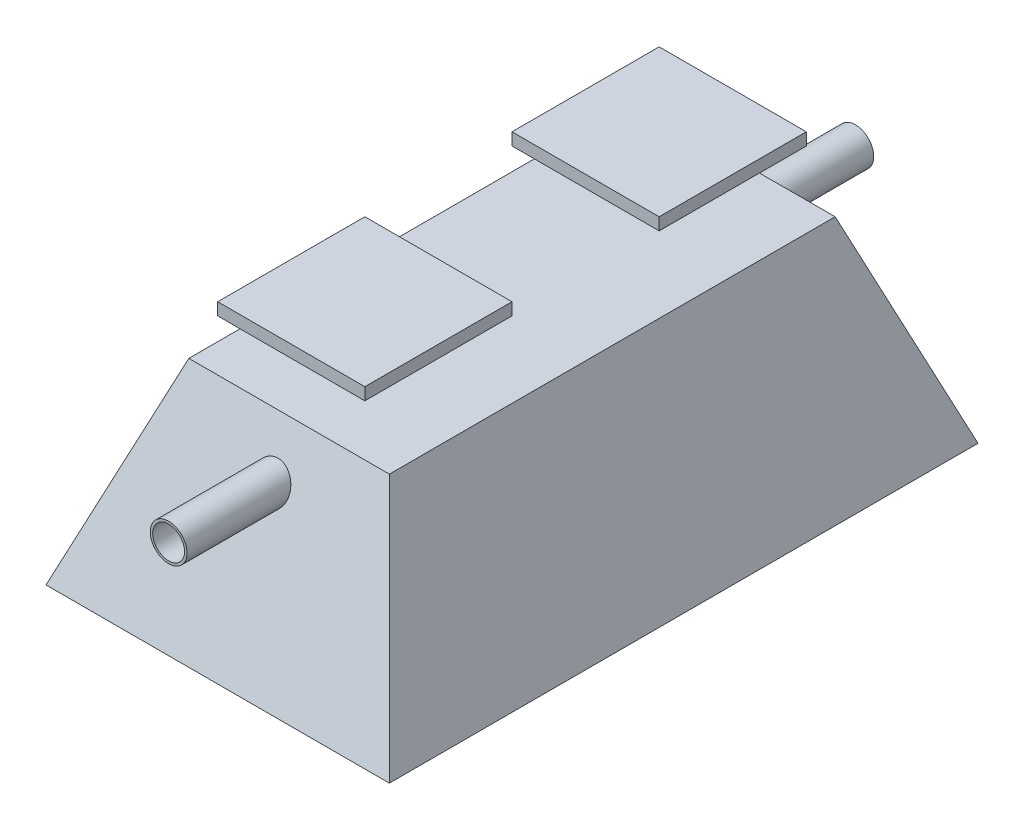
SolidWorks part; units mm, degrees
ref_plane "Front" through (0, 0, 0) normal (0, 0, 1) x (1, 0, 0)
ref_plane "Top" through (0, 0, 0) normal (0, 1, 0) x (1, 0, 0)
ref_plane "Right" through (0, 0, 0) normal (1, 0, 0) x (0, 0, -1)
sketch "Sketch1" plane through (0, 0, 0) normal (0, 1, 0) x (1, 0, 0)
  line L1 (-177.8, 304.8) -> (177.8, 304.8)
  line L2 (-177.8, 304.8) -> (-177.8, -304.8)
  line L3 (-177.8, -304.8) -> (177.8, -304.8)
  line L4 (177.8, 304.8) -> (177.8, -304.8)
  line L5 (-177.8, 304.8) -> (177.8, -304.8) construction
  line L6 (-177.8, -304.8) -> (177.8, 304.8) construction
  point P0 (0, 0)
  dimension "D1" = 609.6
  dimension "D2" = 355.6
extrude "Boss-Extrude1" add sketch "Sketch1" along normal blind 203.2 draft 20
sketch "Sketch2" plane through (0, 0, 0) normal (0, 0, 1) x (1, 0, 0)
  line L0 (0, 152.4) -> (0, 0) construction
  circle A0 centre (0, 152.4) radius 12.7
  circle A1 centre (0, 152.4) radius 19.05
  dimension "D1" = 25.4
  dimension "D3" = 38.1
  dimension "D2" = 152.4
extrude "Boss-Extrude2" add sketch "Sketch2" along normal blind 355.6 and the other way blind 355.6
shell "Shell1" thickness 2.54
sketch "Sketch3" plane through (0, 0, 353.06) normal (0, 0, -1) x (-1, 0, 0)
  circle A1 centre (0, 152.4) radius 16.51
  circle A2 centre (0, 152.4) radius 16.51
  dimension "D1" = 0
extrude "Cut-Extrude1" cut sketch "Sketch3" against normal through all and the other way through all
sketch "Sketch4" plane through (0, 203.2, 0) normal (0, 1, 0) x (1, 0, 0)
  line L0 (0, 0) -> (0, 152.4) construction
  line L1 (0, 0) -> (0, -152.4) construction
  circle A0 centre (0, 152.4) radius 6.35
  circle A1 centre (0, -152.4) radius 6.35
  dimension "D2" = 12.7
  dimension "D3" = 12.7
  dimension "D1" = 152.4
extrude "Boss-Extrude3" add sketch "Sketch4" along normal blind 50.8
sketch "Sketch5" plane through (0, 254, 0) normal (0, 1, 0) x (1, 0, 0)
  line L1 (-76.2, 228.6) -> (76.2, 228.6)
  line L2 (-76.2, 228.6) -> (-76.2, 76.2)
  line L3 (-76.2, 76.2) -> (76.2, 76.2)
  line L4 (76.2, 228.6) -> (76.2, 76.2)
  line L5 (-76.2, 228.6) -> (76.2, 76.2) construction
  line L6 (-76.2, 76.2) -> (76.2, 228.6) construction
  line L7 (-76.2, -76.2) -> (76.2, -76.2)
  line L8 (-76.2, -76.2) -> (-76.2, -228.6)
  line L9 (-76.2, -228.6) -> (76.2, -228.6)
  line L10 (76.2, -76.2) -> (76.2, -228.6)
  line L11 (-76.2, -76.2) -> (76.2, -228.6) construction
  line L12 (-76.2, -228.6) -> (76.2, -76.2) construction
  point P0 (0, 152.4)
  point P6 (0, -152.4)
  dimension "D1" = 152.4
extrude "Boss-Extrude4" add sketch "Sketch5" along normal blind 12.7
sketch "Sketch6" plane through (0, 0, 0) normal (0, -1, 0) x (1, 0, 0)
  line L0 (175.097, -302.097) -> (-175.097, -302.097) construction
  line L1 (175.097, 302.097) -> (175.097, -302.097) construction
  line L2 (-175.097, 302.097) -> (175.097, 302.097) construction
  line L3 (-175.097, -302.097) -> (-175.097, 302.097) construction
  line L4 (175.097, -302.097) -> (-175.097, -302.097)
  line L5 (175.097, 302.097) -> (175.097, -302.097)
  line L6 (-175.097, 302.097) -> (175.097, 302.097)
  line L7 (-175.097, -302.097) -> (-175.097, 302.097)
extrude "Boss-Extrude5" add sketch "Sketch6" against normal blind 2.54 separate body
